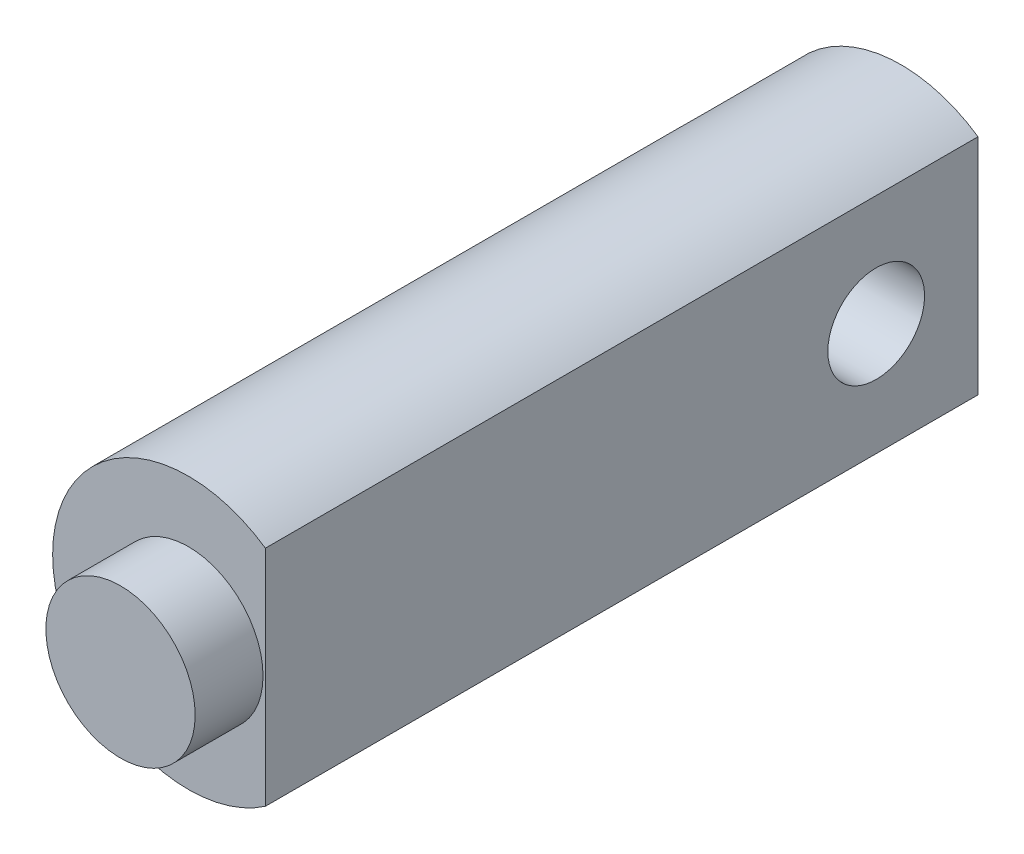
SolidWorks part; units mm, degrees
ref_plane "Front Plane" through (0, 0, 0) normal (0, 0, 1) x (1, 0, 0)
ref_plane "Top Plane" through (0, 0, 0) normal (0, 1, 0) x (1, 0, 0)
ref_plane "Right Plane" through (0, 0, 0) normal (1, 0, 0) x (0, 0, -1)
sketch "Sketch1" plane through (0, 0, 0) normal (0, 0, 1) x (1, 0, 0)
  circle A0 centre (0, 0) radius 11
  dimension "D1" = 22
extrude "Boss-Extrude1" add sketch "Sketch1" along normal blind 10
sketch "Sketch2" plane through (0, 0, 0) normal (0, 0, -1) x (-1, 0, 0)
  circle A0 centre (0, 0) radius 20
  dimension "D1" = 40
extrude "Boss-Extrude2" add sketch "Sketch2" along normal blind 105
sketch "Sketch3" plane through (0, 0, 0) normal (1, 0, 0) x (0, 0, -1)
  line L0 (89.625, 14.75) -> (139.625, 14.75)
  line L1 (89.625, -14.5) -> (139.625, -14.5)
  line L2 (139.625, 14.75) -> (139.625, -14.5)
  line L3 (0, 11) -> (0, -11) construction
  arc A0 (89.625, 14.75) -> (89.625, -14.5) centre (89.625, 0.125) ccw
  point P7 (75, 0.125)
  dimension "D1" = 29.25
  dimension "D2" = 75
extrude "Cut-Extrude1" cut sketch "Sketch3" against normal through all
sketch "Sketch5" plane through (0, 0, 0) normal (-1, 0, 0) x (0, 0, 1)
  line L0 (-75, 0.125) -> (-90, 0.125) construction
  arc A0 (-89.625, -14.5) -> (-89.625, 14.75) centre (-89.625, 0.125) ccw construction
  circle A1 centre (-90, 0.125) radius 7.125
  dimension "D2" = 14.25
  dimension "D1" = 15
extrude "Cut-Extrude2" cut sketch "Sketch5" against normal through all
sketch "Sketch6" plane through (0, 0, -105) normal (0, 0, -1) x (-1, 0, 0)
  line L0 (-11.3464, 16.47) -> (-11.3464, -16.47)
  arc A0 (-11.3464, 16.47) -> (-11.3464, -16.47) centre (0, 0) ccw
extrude "Cut-Extrude3" cut sketch "Sketch6" against normal up to surface (105 mm away) up to face at (11, 0, 0)
